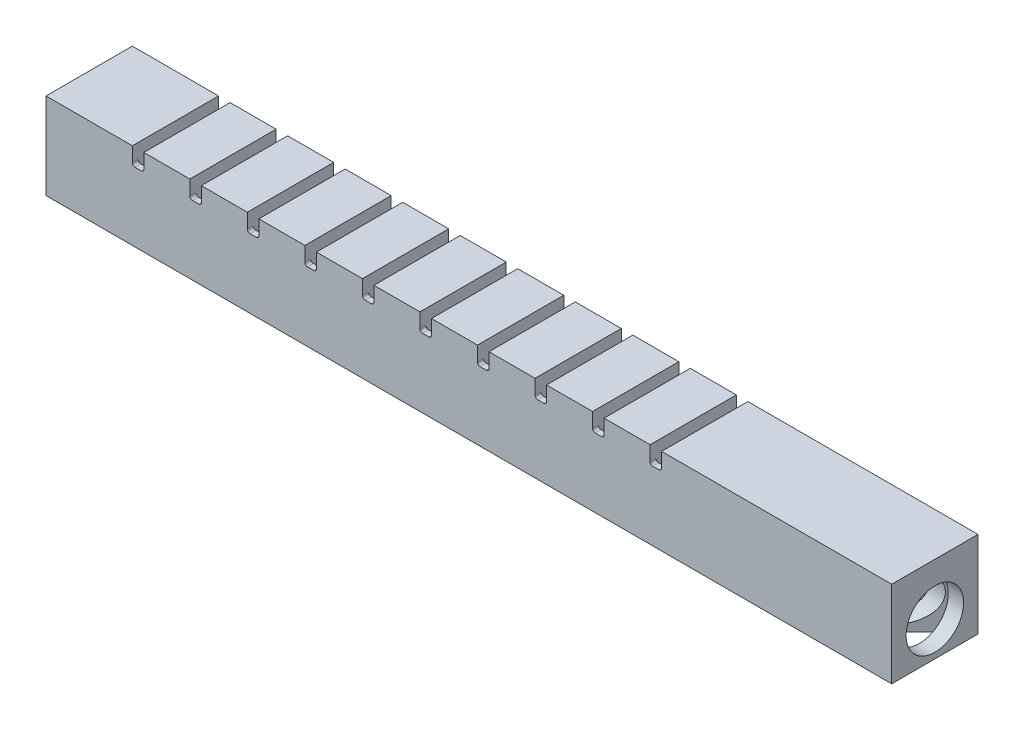
SolidWorks part; units mm, degrees
ref_plane "Front Plane" through (0, 0, 0) normal (0, 0, 1) x (1, 0, 0)
ref_plane "Top Plane" through (0, 0, 0) normal (0, 1, 0) x (1, 0, 0)
ref_plane "Right Plane" through (0, 0, 0) normal (1, 0, 0) x (0, 0, -1)
sketch "Sketch1" plane through (0, 0, 0) normal (0, 0, 1) x (1, 0, 0)
  line L1 (0, 0) -> (8, 0)
  line L2 (0, 0) -> (0, 15)
  line L3 (0, 15) -> (8, 15)
  line L4 (8, 0) -> (8, 15)
  dimension "D1" = 8
  dimension "D2" = 15
extrude "first chamber block" add sketch "Sketch1" along normal blind 15
sketch "Sketch2" plane through (0, 0, 0) normal (0, -1, 0) x (1, 0, 0)
  line L0 (8, 15) -> (8, 0) construction
  line L1 (1, 13) -> (7, 13)
  line L2 (1, 13) -> (1, 2)
  line L3 (1, 2) -> (7, 2)
  line L4 (7, 13) -> (7, 2)
  line L5 (0, 15) -> (0, 0) construction
  line L6 (0, 15) -> (8, 15) construction
  line L7 (0, 0) -> (8, 0) construction
  dimension "D1" = 1
  dimension "D2" = 1
  dimension "D3" = 2
  dimension "D4" = 2
extrude "first chamber cavity" cut sketch "Sketch2" against normal blind 13
sketch "Sketch3" plane through (8, 0, 0) normal (1, 0, 0) x (0, 0, -1)
  line L0 (-15, 0) -> (-15, 15) construction
  line L1 (0, 0) -> (-15, 0)
  line L2 (0, 0) -> (0, 3)
  line L3 (0, 3) -> (-15, 3)
  line L4 (-15, 0) -> (-15, 3)
  dimension "D1" = 3
extrude "chamber spacer" add sketch "Sketch3" along normal blind 2
pattern_linear "pattern chambers" count 11 spacing 10 along (1, 0, 0) of "chamber spacer", "first chamber cavity", "first chamber block"
combine bodies "combine into 1 solid body" operation type add bodies to combine 123 122 121 120 119 118 117 116 115 114 103
sketch "Sketch4" plane through (108, 0, 0) normal (1, 0, 0) x (0, 0, -1)
  line L1 (0, 15) -> (-15, 15)
  line L2 (0, 15) -> (0, 3)
  line L3 (0, 3) -> (-15, 3)
  line L4 (-15, 15) -> (-15, 3)
extrude "thicken end 1" add sketch "Sketch4" along normal up to surface (2 mm away) up to face at (110, 1.5, 7.5)
sketch "Sketch5" plane through (0, 0, 0) normal (-1, 0, 0) x (0, 0, 1)
  line L1 (15, 15) -> (0, 15)
  line L2 (15, 15) -> (15, 0)
  line L3 (15, 0) -> (0, 0)
  line L4 (0, 15) -> (0, 0)
extrude "thicken end 2" add sketch "Sketch5" along normal blind 2
ref_point "center of bottom face"
sketch "Sketch6" plane through (0, 0, 0) normal (0, -1, 0) x (1, 0, 0)
  line L0 (7, 2) -> (7, 13) construction
  line L1 (101, 6.5) -> (7, 6.5)
  line L2 (101, 6.5) -> (101, 8.5)
  line L3 (101, 8.5) -> (7, 8.5)
  line L4 (7, 6.5) -> (7, 8.5)
  line L5 (101, 6.5) -> (7, 8.5) construction
  line L6 (101, 8.5) -> (7, 6.5) construction
  point P0 (54, 7.5)
  dimension "D1" = 2
extrude "central air channel" cut sketch "Sketch6" against normal blind 2
sketch "Skizze3" plane through (8, 0, 0) normal (1, 0, 0) x (0, 0, -1)
  line L0 (-15, 3) -> (-13.5, 3)
  line L1 (0, 3) -> (-15, 3) construction
  line L2 (-13.5, 3) -> (-14, 12.5)
  line L3 (-14, 12.5) -> (-15, 12.5)
  line L4 (-15, 3) -> (-15, 15) construction
  line L5 (-15, 12.5) -> (-15, 3)
  line L6 (-7.5, 15) -> (-7.5, -49985) construction
  line L7 (-15, 15) -> (0, 15) construction
  line L8 (0, 12.5) -> (0, 3)
  line L9 (-1, 12.5) -> (0, 12.5)
  line L10 (-1.5, 3) -> (-1, 12.5)
  line L11 (0, 3) -> (-1.5, 3)
  point P13 (-7.5, 15)
  dimension "D1" = 2.5
  dimension "D2" = 1.5
  dimension "D3" = 1
extrude "Aufsatz-Linear austragen3" add sketch "Skizze3" along normal up to next
sketch "Skizze5" plane through (0, 0, 0) normal (0, 0, -1) x (-1, 0, 0)
  line L0 (-10, 12.5) -> (-10, 3) construction
  line L1 (-10, 12.5) -> (-8, 12.5) construction
  line L2 (-8, 12.5) -> (-8, 3) construction
  line L3 (-10, 12.5) -> (-10, 3) construction
  line L4 (-10, 12.5) -> (-8, 12.5) construction
  line L5 (-8, 12.5) -> (-8, 3) construction
  line L7 (-10, 12.5) -> (-8, 12.5)
  line L8 (-10, 12.5) -> (-10, 12.45)
  line L9 (-9.55, 12) -> (-8.45, 12)
  line L10 (-8, 12.5) -> (-8, 12.45)
  arc A0 (-8.45, 12) -> (-8, 12.45) centre (-8.45, 12.45) ccw
  arc A1 (-10, 12.45) -> (-9.55, 12) centre (-9.55, 12.45) ccw
  point P9 (-8, 12)
  dimension "D1" = 0.45
  dimension "D2" = 0.5
extrude "Schnitt-Linear austragen2" cut sketch "Skizze5" against normal through all
pattern_linear "Lineares Muster8" count 10 spacing 10 along (1, 0, 0) of "Aufsatz-Linear austragen3", "Schnitt-Linear austragen2"
sketch "Sketch17" plane through (110, 0, 0) normal (1, 0, 0) x (0, 0, -1)
  line L4 (0, 0) -> (0, 15)
  line L5 (0, 15) -> (-15, 15)
  line L6 (-15, 15) -> (-15, 0)
  line L7 (-15, 0) -> (0, 0)
  line L8 (0, 0) -> (0, 15)
  line L9 (0, 15) -> (-15, 15)
  line L10 (-15, 15) -> (-15, 0)
  line L11 (-15, 0) -> (0, 0)
  dimension "D1" = 0
extrude "Boss-Extrude1" add sketch "Sketch17" along normal blind 30
sketch "Sketch18" plane through (-2, 0, 0) normal (-1, 0, 0) x (0, 0, 1)
  line L4 (15, 0) -> (15, 15)
  line L5 (15, 15) -> (0, 15)
  line L6 (0, 15) -> (0, 0)
  line L7 (0, 0) -> (15, 0)
  line L8 (15, 0) -> (15, 15)
  line L9 (15, 15) -> (0, 15)
  line L10 (0, 15) -> (0, 0)
  line L11 (0, 0) -> (15, 0)
  dimension "D1" = 0
extrude "Boss-Extrude2" add sketch "Sketch18" along normal blind 5
sketch "Sketch19" plane through (0, 0, 0) normal (0, -1, 0) x (1, 0, 0)
  line L0 (-7, 15) -> (140, 15) construction
  line L1 (140, 0) -> (107, 0) construction
  line L2 (140, 0) -> (140, 15) construction
  line L3 (140, 15) -> (107, 15) construction
  line L4 (107, 0) -> (107, 15) construction
  line L5 (138, 2) -> (109, 2)
  line L6 (109, 2) -> (109, 13)
  line L7 (138, 13) -> (109, 13)
  line L8 (138, 2) -> (138, 13)
  line L9 (107, 2) -> (107, 13) construction
  line L10 (131.8284, 7.5) -> (137.3284, 2)
  line L11 (134.5, 2) -> (130.4142, 6.0858)
  line L12 (123.5, 13) -> (118, 7.5)
  line L13 (131.8284, 7.5) -> (137.3284, 13)
  line L15 (120.6716, 13) -> (116.5858, 8.9142)
  line L16 (123.5, 15.8284) -> (111.0858, 3.4142) construction
  line L17 (136.668, 8.5647) -> (134.2315, 5.0969) construction
  line L18 (138, 2) -> (137.3284, 2) construction
  line L19 (134.5, 13) -> (130.4142, 8.9142)
  line L20 (123.5, 2) -> (118, 7.5)
  line L21 (137.3284, 2) -> (137.3284, -1.3796) construction
  line L23 (120.6716, 2) -> (116.5858, 6.0858)
  line L25 (138.3045, 7.4149) -> (134.5, 2) construction
  line L27 (130.4142, 6.0858) -> (126.3284, 2)
  line L28 (129, 7.5) -> (123.5, 13)
  line L29 (130.4142, 8.9142) -> (126.3284, 13)
  line L30 (134.5, 2) -> (123.5, 13) construction
  line L31 (129, 7.5) -> (123.5, 2)
  line L32 (134.2315, 5.0969) -> (123.5, 15.8284) construction
  line L33 (115.1716, 7.5) -> (109.6716, 2)
  line L34 (116.5858, 8.9142) -> (112.5, 13)
  line L35 (115.1716, 7.5) -> (109.6716, 13)
  line L36 (116.5858, 6.0858) -> (112.5, 2)
  line L37 (124.5, 3) -> (122.5, 3) construction
  line L38 (123.5, 13) -> (112.5, 2) construction
  line L39 (124.5, 3) -> (124.5, 12)
  line L40 (124.5, 12) -> (122.5, 12) construction
  line L41 (122.5, 3) -> (122.5, 12)
  line L42 (109.6716, 2) -> (109.6716, -1.3796) construction
  line L43 (109, 2) -> (109, -1.3796) construction
  line L44 (138, -1.3796) -> (137.3284, -1.3796) construction
  line L45 (138, -1.3796) -> (138, 2) construction
  line L46 (137.3284, -1.3796) -> (109.6716, -1.3796) construction
  line L47 (109.6716, -1.3796) -> (109, -1.3796) construction
  line L48 (109.6716, 2) -> (109.6716, 13)
  line L49 (137.3284, 2) -> (137.3284, 13)
  dimension "D2" = 2
  dimension "D4" = 2
  dimension "D5" = 2
  dimension "D6" = 45
  dimension "D8" = 2
  dimension "D1" = 2
  dimension "D3" = 2
extrude "Cut-Extrude1" cut sketch "Sketch19" against normal offset from surface (12 mm away) 3 contours L13 L10 L5 L8 L7 | L11 L27 L5 | L29 L19 L7 | L23 L36 L5 | L34 L15 L7 | L33 L35 L6 | L39 L31 L28 | L20 L41 L12
sketch "Skizze6" plane through (140, 0, 0) normal (1, 0, 0) x (0, 0, -1)
  line L0 (-7.5, 15) -> (-7.5, 0) construction
  line L1 (0, 15) -> (-15, 15) construction
  line L2 (-15, 0) -> (0, 0) construction
  circle A0 centre (-7.5, 6) radius 5
  dimension "D1" = 10
  dimension "D2" = 9
extrude "Schnitt-Linear austragen3" cut sketch "Skizze6" against normal up to surface (39 mm away) up to face at (101, 3.75, 7.5)
